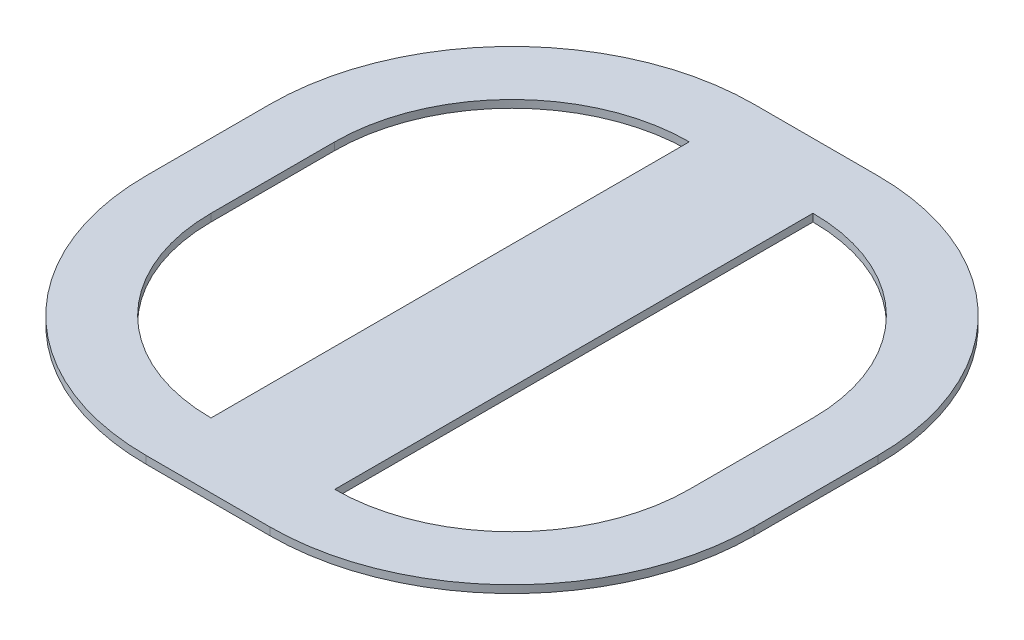
SolidWorks part; units mm, degrees
ref_plane "Front Plane" through (0, 0, 0) normal (0, 0, 1) x (1, 0, 0)
ref_plane "Top Plane" through (0, 0, 0) normal (0, 1, 0) x (1, 0, 0)
ref_plane "Right Plane" through (0, 0, 0) normal (1, 0, 0) x (0, 0, -1)
sketch "Sketch1" plane through (0, 0, 0) normal (0, 1, 0) x (1, 0, 0)
  line L0 (0, 0) -> (0, 19.05)
  line L1 (37.3, 56.35) -> (56.35, 56.35)
  line L2 (93.65, 19.05) -> (93.65, 0)
  line L3 (56.35, -37.3) -> (37.3, -37.3)
  line L4 (10, 0) -> (10, 19.05)
  line L5 (37.3, 46.35) -> (56.35, 46.35)
  line L6 (83.65, 19.05) -> (83.65, 0)
  line L7 (56.35, -27.3) -> (37.3, -27.3)
  arc A0 (0, 19.05) -> (37.3, 56.35) centre (37.3, 19.05) cw
  arc A1 (56.35, 56.35) -> (93.65, 19.05) centre (56.35, 19.05) cw
  arc A2 (93.65, 0) -> (56.35, -37.3) centre (56.35, 0) cw
  arc A3 (37.3, -37.3) -> (0, 0) centre (37.3, 0) cw
  arc A4 (10, 19.05) -> (37.3, 46.35) centre (37.3, 19.05) cw
  arc A5 (56.35, 46.35) -> (83.65, 19.05) centre (56.35, 19.05) cw
  arc A6 (83.65, 0) -> (56.35, -27.3) centre (56.35, 0) cw
  arc A7 (37.3, -27.3) -> (10, 0) centre (37.3, 0) cw
  point P12 (0, 0)
  point P14 (0, 0)
  dimension "D2" = 19.05
  dimension "D1" = 93.65
  dimension "D3" = 10
extrude "Boss-Extrude1" add sketch "Sketch1" along normal blind 1.175
sketch "Sketch4" plane through (0, 0, -46.35) normal (0, 0, 1) x (1, 0, 0)
  line L0 (37.3, 0) -> (37.3, 1.175)
  line L1 (37.3, 1.175) -> (56.35, 1.175)
  line L2 (56.35, 1.175) -> (56.35, 0)
  line L3 (56.35, 0) -> (37.3, 0)
extrude "Boss-Extrude2" add sketch "Sketch4" along normal up to surface (73.65 mm away) up to face at (46.825, 0.5875, 27.3)
